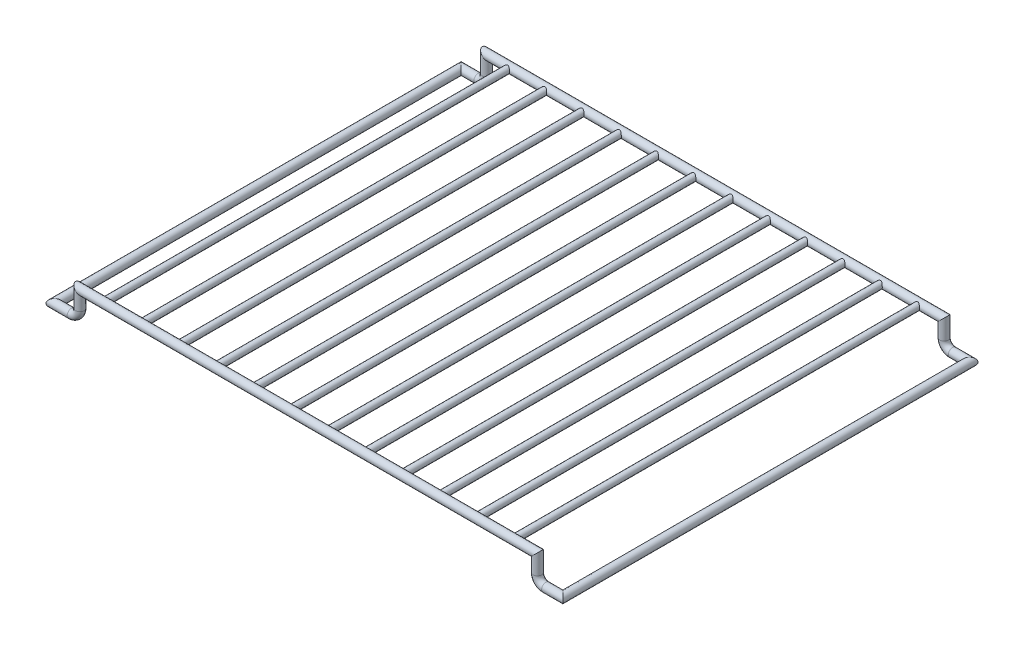
SolidWorks part; units mm, degrees
ref_plane "Front" through (0, 0, 0) normal (0, 0, 1) x (1, 0, 0)
ref_plane "Top" through (0, 0, 0) normal (0, 1, 0) x (1, 0, 0)
ref_plane "Right" through (0, 0, 0) normal (1, 0, 0) x (0, 0, -1)
sketch3d "3D草图1"
  line L0 (0, 0, 0) -> (135, 0, 0)
  line L1 (135, 0, 0) -> (135, -10, 0)
  line L2 (140, -15, 0) -> (150, -15, 0)
  line L3 (150, -15, 0) -> (150, -15, 240)
  line L4 (150, -15, 240) -> (140, -15, 240)
  line L5 (135, -10, 240) -> (135, 0, 240)
  line L6 (135, 0, 240) -> (0, 0, 240)
  arc A0 (135, -10, 0) -> (140, -15, 0) centre (140, -10, 0) ccw
  arc A1 (140, -15, 240) -> (135, -10, 240) centre (140, -10, 240) ccw
  point P11 (135, -15, 0)
  point P12 (140, -10, 5)
  point P15 (135, -15, 240)
  point P16 (140, -10, 235)
  dimension "D8" = 5
  dimension "D1" = 135
  dimension "D2" = 15
  dimension "D3" = 15
  dimension "D4" = 240
  dimension "D5" = 15
  dimension "D6" = 15
  dimension "D7" = 135
sketch "草图1" plane through (0, 0, 0) normal (1, 0, 0) x (0, 0, -1)
  circle A0 centre (0, 0) radius 2.5
  dimension "D1" = 5
sweep "扫描1" add profiles "草图1" path "3D草图1"
sketch "草图2" plane through (0, 0, 0) normal (0, 0, 1) x (1, 0, 0)
  circle A0 centre (11, 0) radius 2
  dimension "D2" = 4
  dimension "D1" = 11
extrude "凸台-拉伸2" add sketch "草图2" along normal up to surface (237.5 mm away)
pattern_linear "阵列(线性)1" count 6 spacing 22 along (1, 0, 0) of "凸台-拉伸2"
mirror "镜向1" about plane through (0, 0, 0) normal (1, 0, 0) of bodies 104
